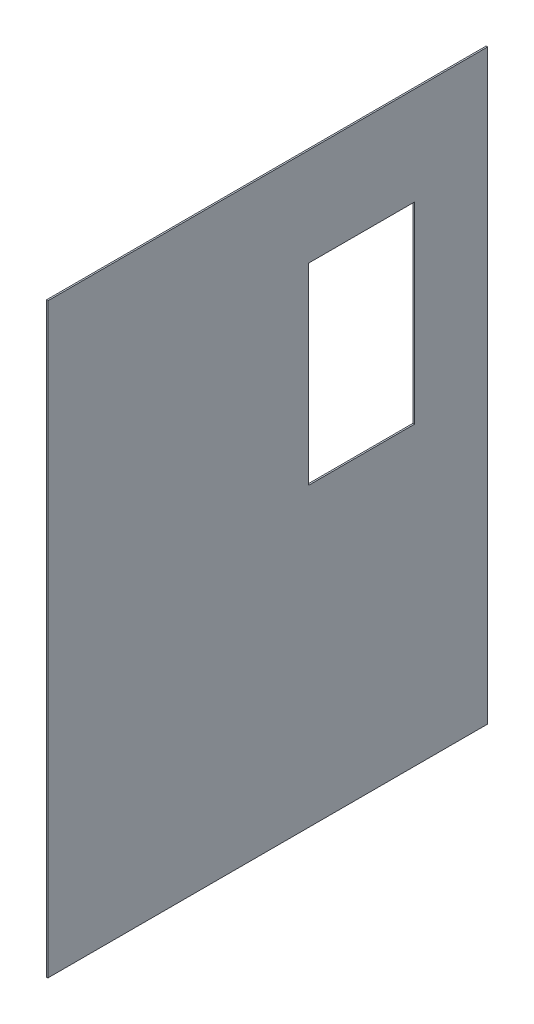
SolidWorks part; units mm, degrees
material "Alloy Steel"
ref_plane "Front Plane" through (0, 0, 0) normal (0, 0, 1) x (1, 0, 0)
ref_plane "Top Plane" through (0, 0, 0) normal (0, 1, 0) x (1, 0, 0)
ref_plane "Right Plane" through (0, 0, 0) normal (1, 0, 0) x (0, 0, -1)
sketch "Sketch1" plane through (0, 0, 0) normal (1, 0, 0) x (0, 0, -1)
  line L1 (457.2, 609.6) -> (-457.2, 609.6)
  line L2 (457.2, 609.6) -> (457.2, -609.6)
  line L3 (457.2, -609.6) -> (-457.2, -609.6)
  line L4 (-457.2, 609.6) -> (-457.2, -609.6)
  line L5 (457.2, 609.6) -> (-457.2, -609.6) construction
  line L6 (457.2, -609.6) -> (-457.2, 609.6) construction
  point P0 (0, 0)
  dimension "D1" = 914.4
  dimension "D2" = 1219.2
extrude "Plate_Base" add sketch "Sketch1" along normal mid plane 3.175
sketch "Sketch4" plane through (0, 0, 0) normal (1, 0, 0) x (0, 0, -1)
  line L0 (457.2, 609.6) -> (-457.2, 609.6) construction
  line L1 (84.8, 406.4) -> (304.8, 406.4)
  line L2 (84.8, 406.4) -> (84.8, 6.4)
  line L3 (84.8, 6.4) -> (304.8, 6.4)
  line L4 (304.8, 406.4) -> (304.8, 6.4)
  line L5 (84.8, 406.4) -> (304.8, 6.4) construction
  line L6 (84.8, 6.4) -> (304.8, 406.4) construction
  line L7 (457.2, -609.6) -> (457.2, 609.6) construction
  point P0 (194.8, 206.4)
  dimension "D1" = 220
  dimension "D2" = 400
  dimension "D3" = 203.2
  dimension "D4" = 152.4
extrude "Tank_Hole" cut sketch "Sketch4" against normal through all both and the other way through all
